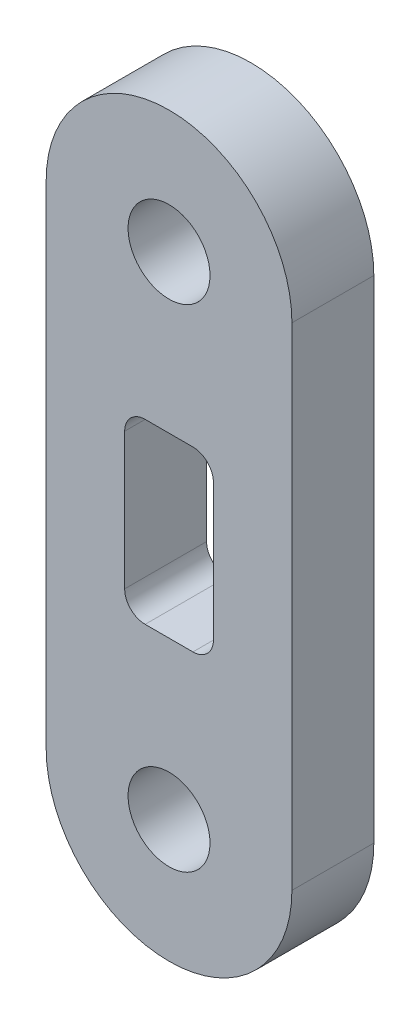
SolidWorks part; units mm, degrees
ref_plane "Alzado" through (0, 0, 0) normal (0, 0, 1) x (1, 0, 0)
ref_plane "Planta" through (0, 0, 0) normal (0, 1, 0) x (1, 0, 0)
ref_plane "Vista lateral" through (0, 0, 0) normal (1, 0, 0) x (0, 0, -1)
sketch "Model" plane through (0, 0, 0) normal (0, 0, 1) x (1, 0, 0)
  line L0 (213.2508, 152.4285) -> (213.2508, 170.4285)
  line L1 (204.2508, 170.4285) -> (204.2508, 152.4285)
  line L2 (207.1258, 158.9285) -> (207.1258, 163.9285)
  line L3 (207.8758, 164.6785) -> (209.6258, 164.6785)
  line L4 (210.3758, 163.9285) -> (210.3758, 158.9285)
  line L5 (209.6258, 158.1785) -> (207.8758, 158.1785)
  circle A0 centre (208.7508, 152.4285) radius 1.5
  circle A1 centre (208.7508, 170.4285) radius 1.5
  arc A2 (204.2508, 152.4285) -> (213.2508, 152.4285) centre (208.7508, 152.4285) ccw
  arc A3 (213.2508, 170.4285) -> (204.2508, 170.4285) centre (208.7508, 170.4285) ccw
  arc A4 (207.8758, 164.6785) -> (207.1258, 163.9285) centre (207.8758, 163.9285) ccw
  arc A5 (210.3758, 163.9285) -> (209.6258, 164.6785) centre (209.6258, 163.9285) ccw
  arc A6 (209.6258, 158.1785) -> (210.3758, 158.9285) centre (209.6258, 158.9285) ccw
  arc A7 (207.1258, 158.9285) -> (207.8758, 158.1785) centre (207.8758, 158.9285) ccw
extrude "Saliente-Extruir1" add sketch "Model" along normal blind 3
